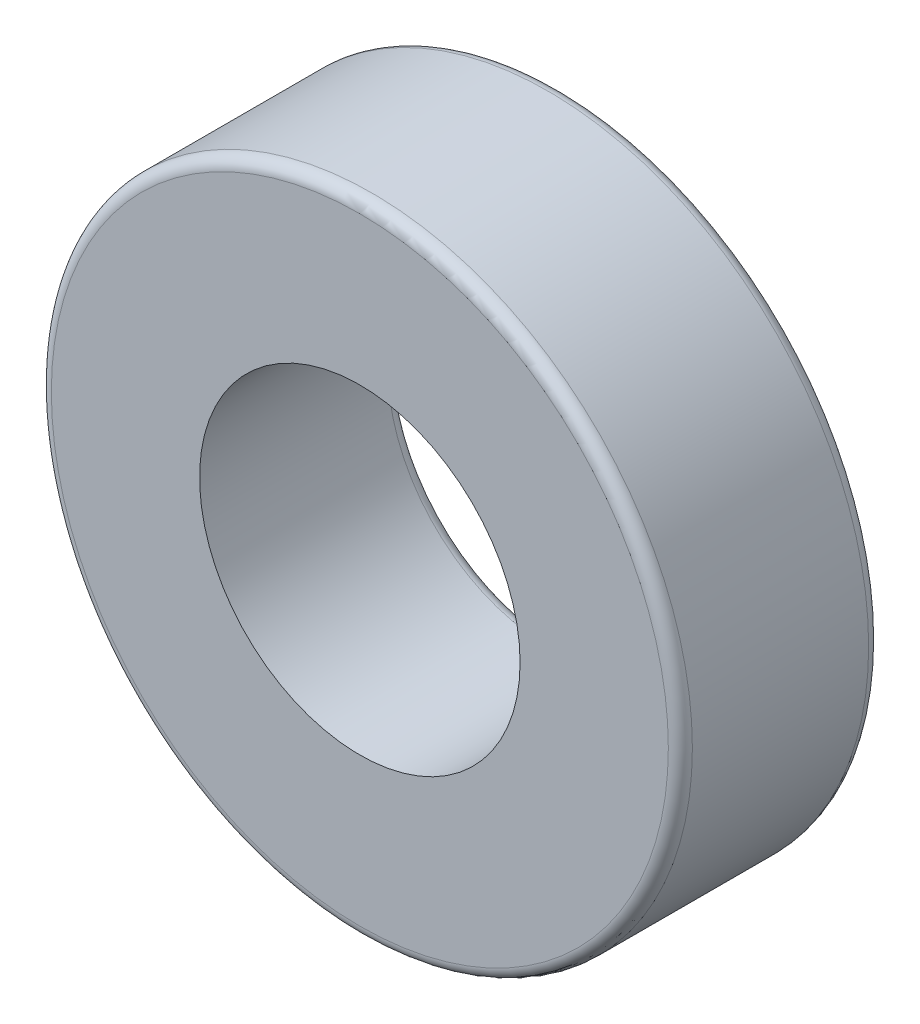
SolidWorks part; units mm, degrees
material "Plain Carbon Steel"
ref_plane "Front Plane" through (0, 0, 0) normal (0, 0, 1) x (1, 0, 0)
ref_plane "Top Plane" through (0, 0, 0) normal (0, 1, 0) x (1, 0, 0)
ref_plane "Right Plane" through (0, 0, 0) normal (1, 0, 0) x (0, 0, -1)
sketch "Sketch1" plane through (0, 0, 0) normal (0, 0, 1) x (1, 0, 0)
  circle A0 centre (0, 0) radius 8
  circle A1 centre (0, 0) radius 4
  dimension "D1" = 8
  dimension "D2" = 16
extrude "Boss-Extrude1" add sketch "Sketch1" along normal mid plane 5
fillet "Fillet2" radius 0.3 3 edges at (8, 0, 2.5) (8, 0, -2.5) (4, 0, -2.5)
